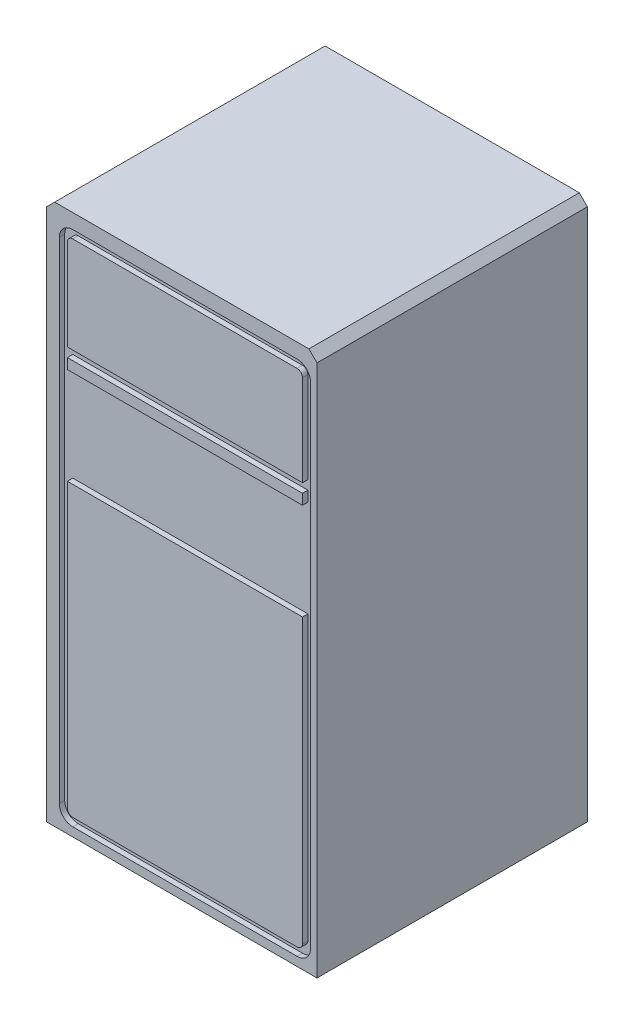
SolidWorks part; units mm, degrees
ref_plane "Alzado" through (0, 0, 0) normal (0, 0, 1) x (1, 0, 0)
ref_plane "Planta" through (0, 0, 0) normal (0, 1, 0) x (1, 0, 0)
ref_plane "Vista lateral" through (0, 0, 0) normal (1, 0, 0) x (0, 0, -1)
sketch "Croquis1" plane through (0, 0, 0) normal (0, 1, 0) x (1, 0, 0)
  line L1 (-500, 500) -> (500, 500)
  line L2 (-500, 500) -> (-500, -500)
  line L3 (-500, -500) -> (500, -500)
  line L4 (500, 500) -> (500, -500)
  line L5 (-500, 500) -> (500, -500) construction
  line L6 (-500, -500) -> (500, 500) construction
  point P0 (0, 0)
  dimension "D1" = 1000
  dimension "D2" = 1000
extrude "Saliente-Extruir1" add sketch "Croquis1" along normal blind 2000
sketch "Croquis2" plane through (0, 0, 500) normal (0, 0, 1) x (1, 0, 0)
  line L0 (-453.1055, 1895.5127) -> (-453.1055, 82.6025)
  line L1 (-403.1055, 1915.5127) -> (426.2386, 1915.5127)
  line L2 (-423.1055, 1895.5127) -> (-423.1055, 1487.1562)
  line L3 (-403.1055, 62.6025) -> (426.2386, 62.6025)
  line L4 (446.2386, 1895.5127) -> (446.2386, 1487.1562)
  line L5 (-423.1055, 1915.5127) -> (446.2386, 62.6025) construction
  line L6 (-423.1055, 62.6025) -> (446.2386, 1915.5127) construction
  line L7 (-403.1055, 32.6025) -> (426.2386, 32.6025)
  line L8 (476.2386, 1895.5127) -> (476.2386, 82.6025)
  line L9 (-403.1055, 1945.5127) -> (426.2386, 1945.5127)
  line L10 (-423.1055, 1129.4484) -> (446.2386, 1129.4484)
  line L12 (446.2386, 1487.1562) -> (-423.1055, 1487.1562)
  line L13 (-423.1055, 1129.4484) -> (-423.1055, 82.6025)
  line L14 (-423.1055, 1895.5127) -> (-423.1055, 82.6025) construction
  line L15 (446.2386, 1129.4484) -> (446.2386, 82.6025)
  line L16 (446.2386, 1895.5127) -> (446.2386, 82.6025) construction
  arc A0 (-423.1055, 82.6025) -> (-403.1055, 62.6025) centre (-403.1055, 82.6025) ccw
  arc A1 (426.2386, 62.6025) -> (446.2386, 82.6025) centre (426.2386, 82.6025) ccw
  arc A2 (-403.1055, 1915.5127) -> (-423.1055, 1895.5127) centre (-403.1055, 1895.5127) ccw
  arc A3 (426.2386, 1915.5127) -> (446.2386, 1895.5127) centre (426.2386, 1895.5127) cw
  arc A4 (-453.1055, 82.6025) -> (-403.1055, 32.6025) centre (-403.1055, 82.6025) ccw
  arc A5 (426.2386, 32.6025) -> (476.2386, 82.6025) centre (426.2386, 82.6025) ccw
  arc A6 (426.2386, 1945.5127) -> (476.2386, 1895.5127) centre (426.2386, 1895.5127) cw
  arc A7 (-403.1055, 1945.5127) -> (-453.1055, 1895.5127) centre (-403.1055, 1895.5127) ccw
  point P0 (11.5665, 989.0576)
  point P5 (0, 0)
  point P34 (415.9471, 1000)
  point P35 (426.0008, 325.7553)
  point P36 (449.3162, 692.8157)
  point P37 (458.6273, 1487.1562)
  point P38 (476.2386, 1129.4484)
  dimension "D1" = 20
  dimension "D2" = 30
extrude "Cortar-Extruir1" cut sketch "Croquis2" against normal blind 20
sketch "Croquis3" plane through (0, 0, 500) normal (0, 0, 1) x (1, 0, 0)
  line L0 (-423.1055, 1559.3618) -> (446.2386, 1559.3618)
  line L1 (-423.1055, 1895.5127) -> (-423.1055, 1487.1562) construction
  line L2 (446.2386, 1487.1562) -> (446.2386, 1895.5127) construction
  line L3 (446.2386, 1559.3618) -> (446.2386, 1525.589)
  line L4 (446.2386, 1525.589) -> (-423.1055, 1525.589)
  line L5 (-423.1055, 1525.589) -> (-423.1055, 1559.3618)
extrude "Cortar-Extruir2" cut sketch "Croquis3" against normal blind 20
chamfer "Chaflán1" distance 30 angle 45 2 edges at (-500, 2000, 0) (500, 2000, 0)
